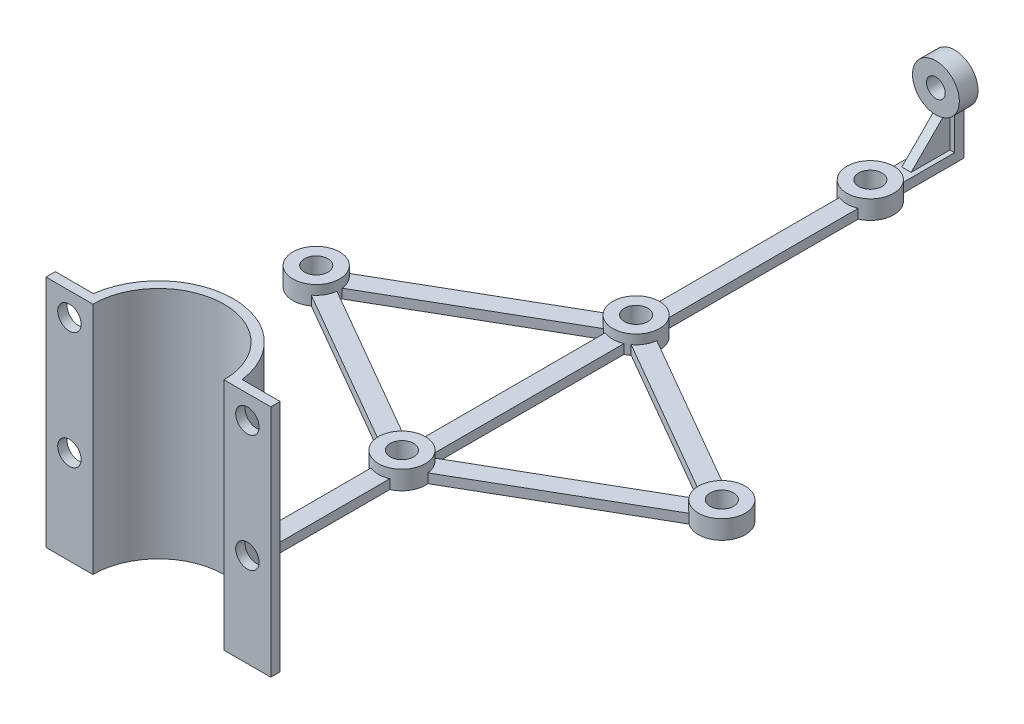
SolidWorks part; units mm, degrees
ref_plane "Спереди" through (0, 0, 0) normal (0, 0, 1) x (1, 0, 0)
ref_plane "Сверху" through (0, 0, 0) normal (0, 1, 0) x (1, 0, 0)
ref_plane "Справа" through (0, 0, 0) normal (1, 0, 0) x (0, 0, -1)
sketch "Эскиз1" plane through (0, 0, 0) normal (0, 1, 0) x (1, 0, 0)
  line L0 (-14, 0) -> (-24, 0)
  line L1 (14, 0) -> (24, 0)
  line L2 (-15.8745, 2) -> (-24, 2)
  line L3 (15.8745, 2) -> (24, 2)
  line L4 (-24, 2) -> (-24, 0)
  line L5 (24, 2) -> (24, 0)
  arc A0 (-14, 0) -> (14, 0) centre (0, 0) cw
  arc A1 (-15.8745, 2) -> (15.8745, 2) centre (0, 0) cw
  dimension "D1" = 10
  dimension "D4" = 14
  dimension "D2" = 10
  dimension "D3" = 2
extrude "Бобышка-Вытянуть1" add sketch "Эскиз1" along normal blind 50
sketch "Эскиз2" plane through (0, 0, 0) normal (0, 0, 1) x (1, 0, 0)
  line L0 (-19, 50) -> (-19, 0) construction
  line L1 (-24, 50) -> (-14, 50) construction
  line L2 (-24, 0) -> (-14, 0) construction
  circle A0 centre (-19, 45) radius 2.5
  circle A1 centre (-19, 20) radius 2.5
  dimension "D1" = 5
  dimension "D2" = 25
extrude "Вырез-Вытянуть1" cut sketch "Эскиз2" against normal through all
mirror "Зеркальное отражение1" about plane through (0, 0, 0) normal (1, 0, 0) of "Вырез-Вытянуть1"
sketch "Эскиз3" plane through (0, 0, 0) normal (0, 1, 0) x (1, 0, 0)
  line L0 (0, 0.2535) -> (0, 129.6974) construction
  line L2 (-2, 168) -> (2, 168)
  line L3 (-2, 168) -> (-2, 14)
  line L4 (-2, 14) -> (2, 14)
  line L5 (2, 168) -> (2, 14)
  line L6 (-2, 168) -> (2, 14) construction
  line L7 (-2, 14) -> (2, 168) construction
  arc A1 (14, 0) -> (-14, 0) centre (0, 0) ccw construction
  point P1 (0, 91)
  dimension "D1" = 4
  dimension "D2" = 154
extrude "Бобышка-Вытянуть2" add sketch "Эскиз3" along normal blind 2
sketch "Эскиз4" plane through (0, 0, 0) normal (0, 1, 0) x (1, 0, 0)
  line L0 (0, 0) -> (0, 202.0606) construction
  circle A0 centre (0, 52) radius 5
  circle A1 centre (0, 102) radius 5
  circle A2 centre (0, 152) radius 5
  dimension "D1" = 52
  dimension "D2" = 50
  dimension "D3" = 50
extrude "Бобышка-Вытянуть3" add sketch "Эскиз4" along normal blind 4
sketch "Эскиз9" plane through (0, 0, 0) normal (0, 1, 0) x (1, 0, 0)
  line L0 (0, 141.0472) -> (0, 14.3903) construction
  circle A0 centre (-43.3013, 77) radius 5
  circle A1 centre (0, 102) radius 5 construction
  circle A2 centre (0, 52) radius 5 construction
  circle A3 centre (43.3013, 77) radius 5
  dimension "D1" = 50
  dimension "D2" = 50
extrude "Бобышка-Вытянуть7" add sketch "Эскиз9" along normal blind 4 separate body
sketch "Эскиз10" plane through (0, 0, 0) normal (0, 1, 0) x (1, 0, 0)
  line L0 (0, 102) -> (-43.3013, 77) construction
  line L1 (-43.3013, 77) -> (0, 52) construction
  line L2 (0, 52) -> (43.3013, 77) construction
  line L3 (43.3013, 77) -> (0, 102) construction
  line L4 (0, 104.3094) -> (-47.3013, 77)
  line L5 (-47.3013, 77) -> (0, 49.6906)
  line L6 (0, 49.6906) -> (47.3013, 77)
  line L7 (47.3013, 77) -> (0, 104.3094)
  line L8 (0, 99.6906) -> (-39.3013, 77)
  line L9 (-39.3013, 77) -> (0, 54.3094)
  line L10 (0, 54.3094) -> (39.3013, 77)
  line L11 (39.3013, 77) -> (0, 99.6906)
  dimension "D1" = 2
  dimension "D2" = 2
extrude "Бобышка-Вытянуть8" add sketch "Эскиз10" along normal blind 2
sketch "Эскиз5" plane through (0, 0, 0) normal (0, 1, 0) x (1, 0, 0)
  circle A0 centre (0, 102) radius 2.5
  circle A1 centre (0, 52) radius 2.5
  circle A2 centre (0, 152) radius 2.5
  circle A3 centre (-43.3013, 77) radius 2.5
  circle A4 centre (43.3013, 77) radius 2.5
extrude "Вырез-Вытянуть3" cut sketch "Эскиз5" along normal through all
sketch "Эскиз11" plane through (0, 0, 0) normal (0, 1, 0) x (1, 0, 0)
  line L0 (0, 170) -> (0, 168) construction
  line L1 (-2, 168) -> (2, 168)
  line L2 (-2, 168) -> (-2, 170)
  line L3 (-2, 170) -> (2, 170)
  line L4 (2, 168) -> (2, 170)
  line L5 (0, 167.1635) -> (0, 171.5139) construction
  dimension "D1" = 2
  dimension "D2" = 4
extrude "Бобышка-Вытянуть9" add sketch "Эскиз11" along normal blind 10
sketch "Эскиз12" plane through (0, 0, -170) normal (0, 0, -1) x (-1, 0, 0)
  circle A0 centre (0, 14) radius 5
  dimension "D1" = 14
extrude "Бобышка-Вытянуть10" add sketch "Эскиз12" against normal blind 4
sketch "Эскиз13" plane through (0, 0, -170) normal (0, 0, -1) x (-1, 0, 0)
  circle A0 centre (0, 14) radius 2
extrude "Вырез-Вытянуть4" cut sketch "Эскиз13" against normal up to next
sketch "Эскиз15" plane through (0, 0, 0) normal (1, 0, 0) x (0, 0, -1)
  line L0 (166.4601, 8.7373) -> (160.2869, 2.564)
rib "Ребро2" sketch "Эскиз15" sketch "Эскиз15" thickness 2 extrusion direction parallel to sketch draft on no parameters "D1"=2
sketch "Эскиз16" plane through (0, 0, 0) normal (1, 0, 0) x (0, 0, -1)
  line L0 (16.2589, 9.5086) -> (23.1337, 2.6338)
rib "Ребро7" sketch "Эскиз16" sketch "Эскиз16" thickness 2 extrusion direction parallel to sketch draft on no parameters "D1"=2
